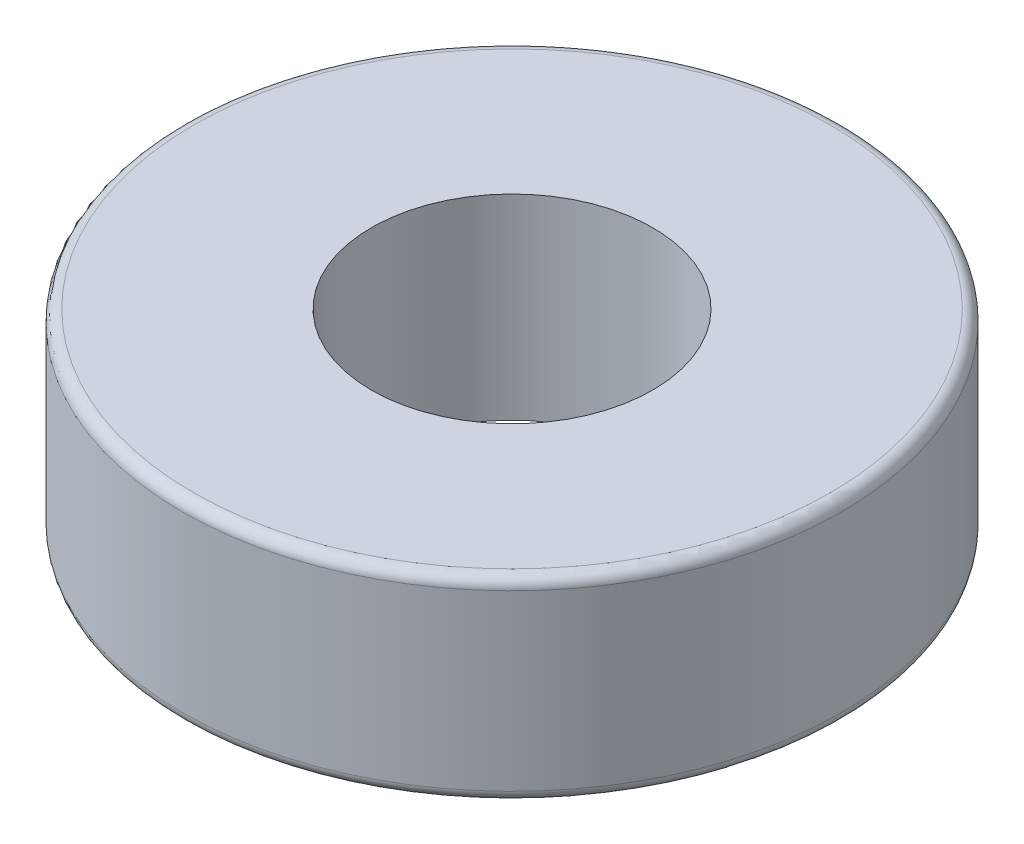
SolidWorks part; units mm, degrees
material "Alloy Steel"
ref_plane "X-Y Datum" through (0, 0, 0) normal (0, 0, 1) x (1, 0, 0)
ref_plane "X-Z Datum" through (0, 0, 0) normal (0, 1, 0) x (1, 0, 0)
ref_plane "Y-Z Datum" through (0, 0, 0) normal (1, 0, 0) x (0, 0, -1)
sketch "Sketch1" plane through (0, 0, 0) normal (0, 1, 0) x (1, 0, 0)
  circle A0 centre (0, 0) radius 23.495
  circle A1 centre (0, 0) radius 10.033
  dimension "D1" = 46.99
  dimension "D2" = 20.066
extrude "Boss-Extrude1" add sketch "Sketch1" along normal blind 13.97
fillet "Fillet1" radius 0.7937 2 edges at (0, 0, 23.495) (0, 13.97, 23.495)
